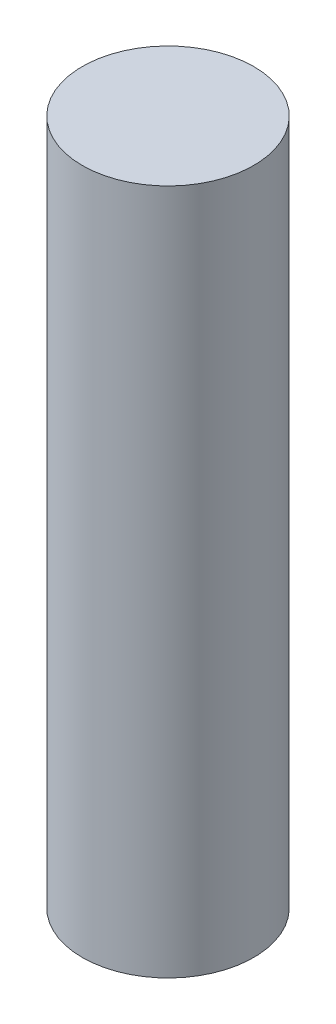
SolidWorks part; units mm, degrees
ref_plane "Front Plane" through (0, 0, 0) normal (0, 0, 1) x (1, 0, 0)
ref_plane "Top Plane" through (0, 0, 0) normal (0, 1, 0) x (1, 0, 0)
ref_plane "Right Plane" through (0, 0, 0) normal (1, 0, 0) x (0, 0, -1)
sketch "Sketch1" plane through (0, 0, 0) normal (0, 1, 0) x (1, 0, 0)
  circle A0 centre (0, 0) radius 5
  dimension "D1" = 10
extrude "Boss-Extrude1" add sketch "Sketch1" along normal blind 40
